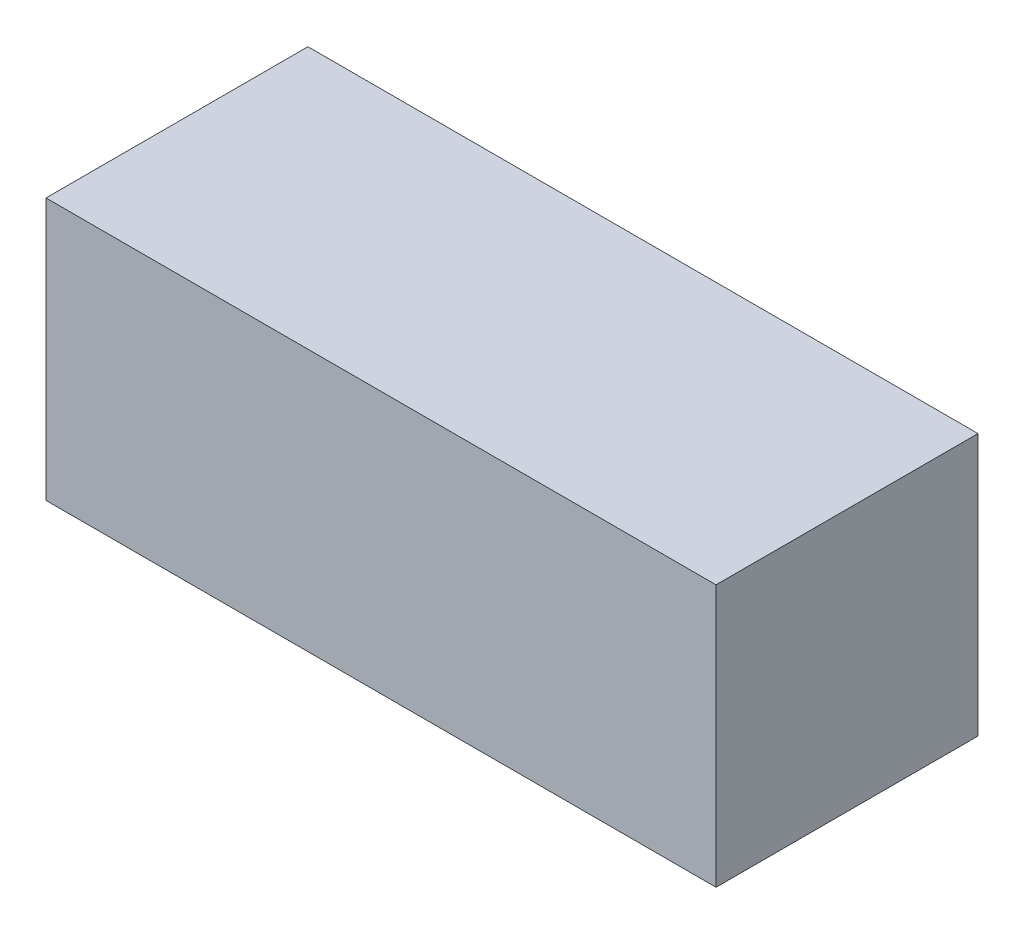
SolidWorks part; units mm, degrees
ref_plane "Alzado" through (0, 0, 0) normal (0, 0, 1) x (1, 0, 0)
ref_plane "Planta" through (0, 0, 0) normal (0, 1, 0) x (1, 0, 0)
ref_plane "Vista lateral" through (0, 0, 0) normal (1, 0, 0) x (0, 0, -1)
sketch "Croquis1" plane through (0, 0, 0) normal (0, 0, 1) x (1, 0, 0)
  line L0 (-83.2649, -34.1746) -> (-6.5293, -34.1746)
  line L1 (-6.5293, -34.1746) -> (-6.5293, -4.1746)
  line L2 (-83.2649, -34.1746) -> (-83.2649, -4.1746)
  line L3 (-83.2649, -4.1746) -> (-6.5293, -4.1746)
  dimension "D1" = 6.5293
  dimension "D2" = 83.2649
  dimension "D3" = 4.1746
  dimension "D4" = 34.1746
extrude "Saliente-Extruir1" add sketch "Croquis1" along normal blind 30
